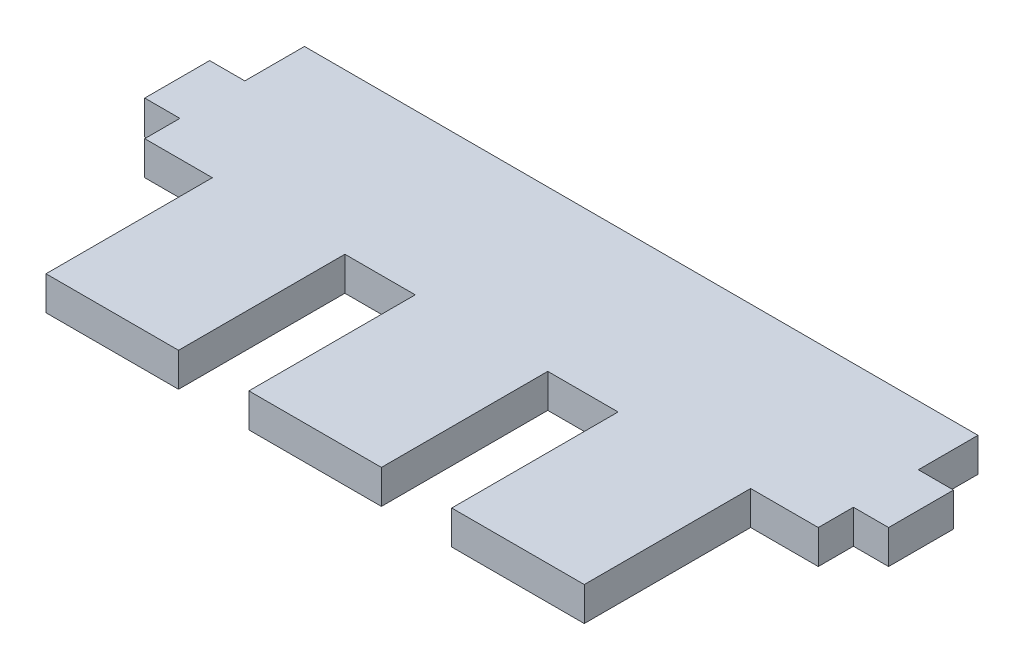
SolidWorks part; units mm, degrees
ref_plane "Front Plane" through (0, 0, 0) normal (0, 0, 1) x (1, 0, 0)
ref_plane "Top Plane" through (0, 0, 0) normal (0, 1, 0) x (1, 0, 0)
ref_plane "Right Plane" through (0, 0, 0) normal (1, 0, 0) x (0, 0, -1)
sketch "Sketch1" plane through (0, 0, 0) normal (0, 1, 0) x (1, 0, 0)
  line L2 (-69.85, -28.575) -> (-69.85, 28.575)
  line L3 (-69.85, 28.575) -> (69.85, 28.575)
  line L4 (69.85, -28.575) -> (69.85, 28.575)
  line L5 (-69.85, -28.575) -> (69.85, 28.575) construction
  line L6 (-69.85, 28.575) -> (69.85, -28.575) construction
  line L11 (-69.85, -28.575) -> (69.85, -28.575)
  point P0 (0, 0)
  dimension "D1" = 57.15
  dimension "D2" = 139.7
extrude "Boss-Extrude1" add sketch "Sketch1" along normal blind 6.35
sketch "Sketch3" plane through (0, 0, 0) normal (0, 1, 0) x (1, 0, 0)
  line L0 (-69.85, -28.575) -> (69.85, -28.575) construction
  line L1 (-50.546, -28.575) -> (-50.546, -59.817)
  line L2 (-50.546, -59.817) -> (-25.654, -59.817)
  line L3 (-25.654, -59.817) -> (-25.654, -28.575)
  line L4 (-25.654, -28.575) -> (-50.546, -28.575)
  line L5 (-12.446, -28.575) -> (-12.446, -59.817)
  line L6 (-12.446, -59.817) -> (12.446, -59.817)
  line L7 (12.446, -59.817) -> (12.446, -28.575)
  line L8 (12.446, -28.575) -> (-12.446, -28.575)
  line L9 (25.654, -28.575) -> (25.654, -59.817)
  line L10 (25.654, -59.817) -> (50.546, -59.817)
  line L11 (50.546, -59.817) -> (50.546, -28.575)
  line L12 (50.546, -28.575) -> (25.654, -28.575)
  line L21 (63.754, -28.575) -> (63.754, -59.817) [skipped]
  line L22 (63.754, -59.817) -> (88.646, -59.817) [skipped]
  line L23 (88.646, -59.817) -> (88.646, -28.575) [skipped]
  line L24 (88.646, -28.575) -> (63.754, -28.575) [skipped]
  line L25 (101.854, -28.575) -> (101.854, -59.817) [skipped]
  line L26 (101.854, -59.817) -> (126.746, -59.817) [skipped]
  line L27 (126.746, -59.817) -> (126.746, -28.575) [skipped]
  line L28 (126.746, -28.575) -> (101.854, -28.575) [skipped]
  point P0 (-38.1, -28.575)
  point P6 (0, -28.575)
  point P14 (38.1, -28.575)
  point P20 (114.3, -28.575)
  point P21 (76.2, -28.575)
  dimension "D1" = 24.892
  dimension "D2" = 31.242
  dimension "D3" = 38.1
  dimension "D4" = 5
extrude "Boss-Extrude2" add sketch "Sketch3" along normal blind 6.35
sketch "Sketch4" plane through (0, 0, 0) normal (0, 1, 0) x (1, 0, 0)
  line L0 (69.85, 28.575) -> (-69.85, 28.575) construction
  line L8 (0, 0) -> (0, 63.6475) construction
  line L13 (69.85, -28.575) -> (69.85, 28.575) construction
  line L14 (63.246, 28.829) -> (76.454, 28.829)
  line L30 (63.246, 28.829) -> (63.246, 15.621)
  line L31 (63.246, 15.621) -> (76.454, 15.621)
  line L32 (76.454, 28.829) -> (76.454, 15.621)
  line L33 (63.246, 28.829) -> (76.454, 15.621) construction
  line L34 (63.246, 15.621) -> (76.454, 28.829) construction
  line L35 (-63.246, -35.179) -> (-76.454, -21.971) construction
  line L38 (-63.246, -21.971) -> (-76.454, -35.179) construction
  line L39 (-63.246, -9.779) -> (-76.454, 3.429) construction
  line L44 (-63.246, 3.429) -> (-76.454, -9.779) construction
  line L45 (-63.246, 15.621) -> (-76.454, 28.829) construction
  line L50 (-63.246, 28.829) -> (-76.454, 15.621) construction
  line L51 (-76.454, -21.971) -> (-76.454, -35.179)
  line L52 (63.246, 3.429) -> (76.454, 3.429)
  line L53 (63.246, 3.429) -> (63.246, -9.779)
  line L54 (63.246, -9.779) -> (76.454, -9.779)
  line L55 (76.454, 3.429) -> (76.454, -9.779)
  line L56 (63.246, 3.429) -> (76.454, -9.779) construction
  line L57 (63.246, -9.779) -> (76.454, 3.429) construction
  line L58 (63.246, -21.971) -> (76.454, -21.971)
  line L59 (63.246, -21.971) -> (63.246, -35.179)
  line L60 (63.246, -35.179) -> (76.454, -35.179)
  line L61 (76.454, -21.971) -> (76.454, -35.179)
  line L62 (63.246, -21.971) -> (76.454, -35.179) construction
  line L63 (63.246, -35.179) -> (76.454, -21.971) construction
  line L64 (-63.246, -35.179) -> (-76.454, -35.179)
  line L65 (-203.454, 28.829) -> (-190.246, 28.829) [skipped]
  line L66 (-203.454, 28.829) -> (-203.454, 15.621) [skipped]
  line L67 (-203.454, 15.621) -> (-190.246, 15.621) [skipped]
  line L68 (-190.246, 28.829) -> (-190.246, 15.621) [skipped]
  line L69 (-203.454, 3.429) -> (-190.246, 3.429) [skipped]
  line L70 (-203.454, 3.429) -> (-203.454, -9.779) [skipped]
  line L71 (-203.454, -9.779) -> (-190.246, -9.779) [skipped]
  line L72 (-190.246, 3.429) -> (-190.246, -9.779) [skipped]
  line L73 (-203.454, -21.971) -> (-190.246, -21.971) [skipped]
  line L74 (-203.454, -21.971) -> (-203.454, -35.179) [skipped]
  line L75 (-203.454, -35.179) -> (-190.246, -35.179) [skipped]
  line L76 (-190.246, -21.971) -> (-190.246, -35.179) [skipped]
  line L77 (-203.454, 28.829) -> (-190.246, 15.621) construction
  line L78 (-203.454, 15.621) -> (-190.246, 28.829) construction
  line L79 (-203.454, 3.429) -> (-190.246, -9.779) construction
  line L80 (-203.454, -9.779) -> (-190.246, 3.429) construction
  line L81 (-203.454, -21.971) -> (-190.246, -35.179) construction
  line L82 (-203.454, -35.179) -> (-190.246, -21.971) construction
  line L83 (-63.246, -21.971) -> (-63.246, -35.179)
  line L84 (-63.246, -21.971) -> (-76.454, -21.971)
  line L85 (-76.454, 3.429) -> (-76.454, -9.779)
  line L86 (-63.246, -9.779) -> (-76.454, -9.779)
  line L87 (-63.246, 3.429) -> (-63.246, -9.779)
  line L88 (-63.246, 3.429) -> (-76.454, 3.429)
  line L89 (-76.454, 28.829) -> (-76.454, 15.621)
  line L90 (-63.246, 15.621) -> (-76.454, 15.621)
  line L91 (-63.246, 28.829) -> (-63.246, 15.621)
  line L92 (-63.246, 28.829) -> (-76.454, 28.829)
  point P5 (-196.85, -28.575)
  point P6 (-196.85, -3.175)
  point P7 (-196.85, 22.225)
  point P13 (69.85, 22.225)
  point P28 (-69.85, -28.575)
  point P29 (69.85, -3.175)
  point P34 (69.85, -28.575)
  point P36 (-69.85, -3.175)
  point P37 (-69.85, 22.225)
  dimension "D1" = 3
  dimension "D2" = 2
  dimension "D4" = 13.208
  dimension "D6" = 13.208
  dimension "D7" = 6.35
extrude "Cut-Extrude2" cut sketch "Sketch4" along normal through all
sketch "Sketch5" plane through (0, 6.35, 0) normal (0, 1, 0) x (1, 0, 0)
  line L0 (63.246, 28.575) -> (-63.246, 28.575) construction
  line L1 (-139.7688, 28.575) -> (155.6953, 28.575)
  line L2 (-139.7688, 28.575) -> (-139.7688, 15.875)
  line L3 (-139.7688, 15.875) -> (155.6953, 15.875)
  line L4 (155.6953, 28.575) -> (155.6953, 15.875)
  dimension "D1" = 12.7
extrude "Cut-Extrude3" cut sketch "Sketch5" against normal through all
sketch "Sketch6" plane through (0, 6.35, 0) normal (0, 1, 0) x (1, 0, 0)
  line L0 (69.85, 3.429) -> (69.85, 15.621) construction
  line L1 (-69.85, 3.429) -> (69.85, 3.429)
  line L2 (-69.85, 3.429) -> (-69.85, 15.875)
  line L3 (-69.85, 15.875) -> (69.85, 15.875)
  line L4 (69.85, 3.429) -> (69.85, 15.875)
  line L5 (-63.246, 15.875) -> (63.246, 15.875) construction
extrude "Boss-Extrude3" add sketch "Sketch6" against normal up to surface (6.35 mm away) up to face at (0, 0, 18.9547)
sketch "Sketch7" plane through (0, 6.35, 0) normal (0, 1, 0) x (1, 0, 0)
  line L0 (69.85, 3.429) -> (69.85, 15.875) construction
  line L1 (-69.85, 15.875) -> (69.85, 15.875)
  line L2 (-69.85, 15.875) -> (-69.85, 1.425)
  line L3 (-69.85, 1.425) -> (69.85, 1.425)
  line L4 (69.85, 15.875) -> (69.85, 1.425)
  line L5 (-69.85, 15.875) -> (-69.85, 3.429) construction
  line L6 (-69.85, 15.875) -> (69.85, 15.875) construction
  line L7 (-25.654, -28.575) -> (-12.446, -28.575) construction
  dimension "D1" = 30
extrude "Cut-Extrude4" cut sketch "Sketch7" against normal through all
